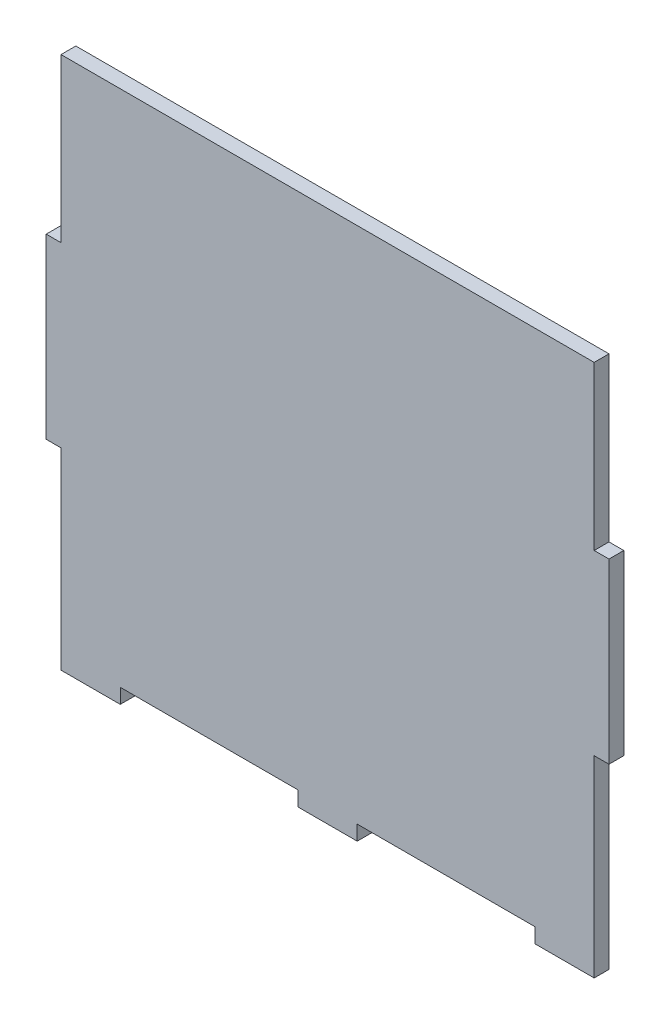
SolidWorks part; units mm, degrees
ref_plane "Front Plane" through (0, 0, 0) normal (0, 0, 1) x (1, 0, 0)
ref_plane "Top Plane" through (0, 0, 0) normal (0, 1, 0) x (1, 0, 0)
ref_plane "Right Plane" through (0, 0, 0) normal (1, 0, 0) x (0, 0, -1)
sketch "Sketch1" plane through (0, 0, 0) normal (0, 0, 1) x (1, 0, 0)
  line L0 (4.191, 181.2138) -> (4.191, -47.3862) construction
  line L1 (-110.109, 181.2138) -> (118.491, 181.2138)
  line L2 (-110.109, 181.2138) -> (-110.109, -47.3862)
  line L3 (-110.109, -47.3862) -> (-84.709, -47.3862)
  line L4 (118.491, 181.2138) -> (118.491, -47.3862)
  line L5 (-110.109, 66.9138) -> (118.491, 66.9138) construction
  line L6 (124.841, 35.1638) -> (118.491, 35.1638)
  line L7 (-116.459, 111.3638) -> (-110.109, 111.3638)
  line L8 (-116.459, 111.3638) -> (-116.459, 35.1638)
  line L9 (-116.459, 35.1638) -> (-110.109, 35.1638)
  line L11 (-8.509, -47.3862) -> (4.191, -47.3862)
  line L12 (93.091, -47.3862) -> (93.091, -41.0362)
  line L13 (-84.709, -47.3862) -> (-84.709, -41.0362)
  line L14 (-84.709, -41.0362) -> (-8.509, -41.0362)
  line L15 (124.841, 111.3638) -> (124.841, 35.1638)
  line L16 (124.841, 111.3638) -> (118.491, 111.3638)
  line L23 (-8.509, -47.3862) -> (-8.509, -41.0362)
  line L24 (93.091, -41.0362) -> (16.891, -41.0362)
  line L25 (16.891, -47.3862) -> (16.891, -41.0362)
  line L26 (16.891, -47.3862) -> (4.191, -47.3862)
  line L27 (118.491, -47.3862) -> (93.091, -47.3862)
  point P17 (0, 0)
  point P29 (-84.709, -44.2112)
  dimension "D1" = 228.6
  dimension "D2" = 228.6
  dimension "D3" = 6.35
  dimension "D4" = 76.2
  dimension "D6" = 25.4
  dimension "D5" = 82.55
extrude "Boss-Extrude2" add sketch "Sketch1" along normal blind 6.35 contours L27 L4 L1 L2 L3 L13 L14 L23 L11 L26 L25 L24 L12 | L8 L9 L2 L7 | L15 L16 L4 L6
equation "\"width\"= 9in"
equation "\"Height\"= 18in"
equation "\"thick\"= 0.25"
equation "\"D1@Sketch1\"=\"width\""
equation "\"D2@Sketch1\"=\"width\""
equation "\"D3@Sketch1\"=\"thick\""
equation "\"D1@Boss-Extrude2\"=\"thick\""
